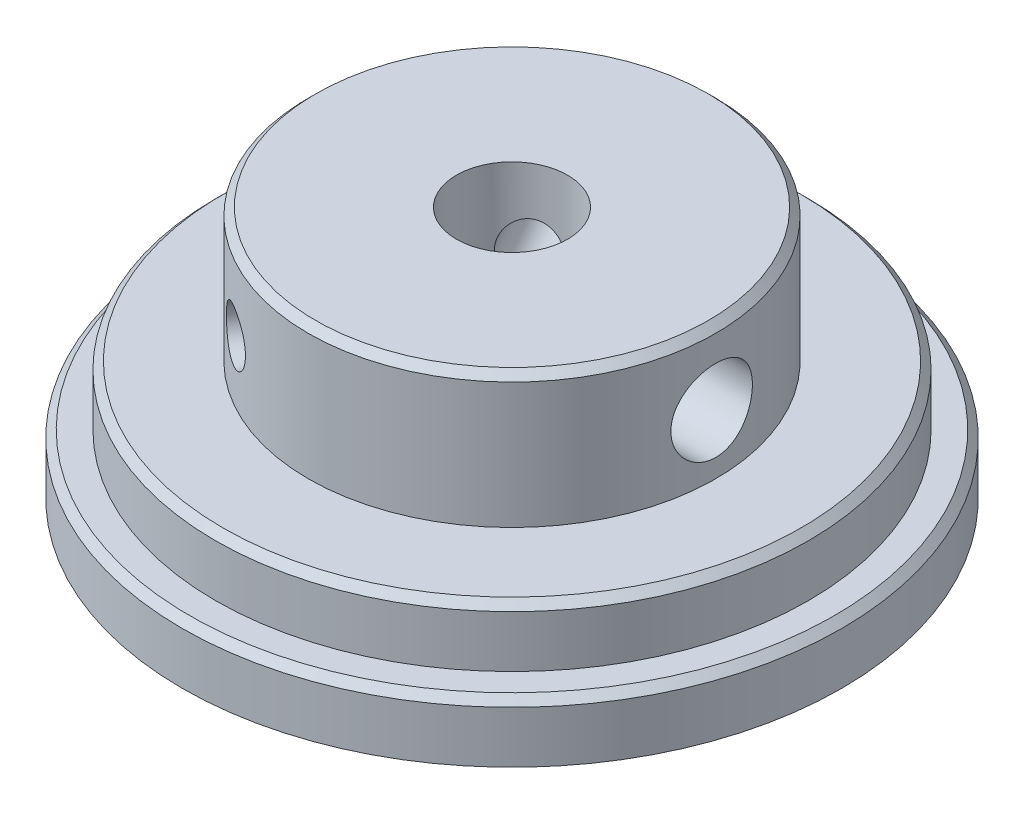
SolidWorks part; units mm, degrees
ref_plane "Piano frontale" through (0, 0, 0) normal (0, 0, 1) x (1, 0, 0)
ref_plane "Piano superiore" through (0, 0, 0) normal (0, 1, 0) x (1, 0, 0)
ref_plane "Piano destro" through (0, 0, 0) normal (1, 0, 0) x (0, 0, -1)
sketch "Schizzo2" plane through (0, 0, 0) normal (0, 0, 1) x (1, 0, 0)
  line L0 (0, 38.3941) -> (0, -24.0435) construction
  line L1 (7.5, 0) -> (44.5, 0)
  line L2 (44.5, 0) -> (44.5, 8)
  line L3 (44.5, 8) -> (40, 8)
  line L4 (40, 8) -> (40, 16)
  line L5 (40, 16) -> (27.5, 16)
  line L6 (27.5, 16) -> (27.5, 34)
  line L7 (27.5, 34) -> (7.5, 34)
  line L8 (7.5, 34) -> (7.5, 0)
  dimension "D1" = 55
  dimension "D2" = 16
  dimension "D3" = 34
  dimension "D4" = 80
  dimension "D5" = 8
  dimension "D6" = 89
  dimension "D7" = 15
revolve "Rivoluzione1" add sketch "Schizzo2" angle 360 about L0
ref_plane "Piano1" through (27.5, 0, 0) normal (1, 0, 0) x (0, 0, -1)
hole_wizard "Foro Ø11.0 (11)-1" positions "Schizzo3" profile "Schizzo4" hole size "Ø11.0" standard "ISO"
sketch "Schizzo3" plane through (27.5, 0, 0) normal (1, 0, 0) x (0, 0, -1)
  line L0 (0, 34) -> (0, 16) construction
  line L1 (27.5, 34) -> (-27.5, 34) construction
  line L2 (40, 16) -> (-40, 16) construction
  point P7 (0, 24)
  dimension "D1" = 10
sketch "Schizzo4" plane through (27.5, 24, 0) normal (0, 1, 0) x (0, 0, -1)
  line L0 (0, 0) -> (0, 20)
  line L1 (0, 20) -> (5.5, 20)
  line L2 (5.5, 20) -> (5.5, 0)
  line L5 (5.5, 0) -> (0, 0)
  line L11 (0, -6.35) -> (0, 107.95) construction
  dimension "Thru Hole Dia." = 11
  dimension "Thru Hole Depth" = 20
ref_plane "Piano2" through (-13.75, 0, 23.8157) normal (-0.5, 0, 0.866) x (0, 1, 0)
hole_wizard "Foro Ø7.0 (7)-1" positions "Schizzo5" profile "Schizzo6" hole size "Ø7.0" standard "ISO"
sketch "Schizzo5" plane through (-13.75, 0, 23.8157) normal (-0.5, 0, 0.866) x (0, 1, 0)
  line L0 (0, 0) -> (34, 0) construction
  line L1 (34, -27.5) -> (34, 27.5) construction
  point P8 (24, 0)
  dimension "D1" = 10
sketch "Schizzo6" plane through (-13.75, 24, 23.8157) normal (0, 1, 0) x (0.866, 0, 0.5)
  line L0 (0, 0) -> (0, 20)
  line L1 (0, 20) -> (3.5, 20)
  line L2 (3.5, 20) -> (3.5, 0)
  line L5 (3.5, 0) -> (0, 0)
  line L11 (0, -6.35) -> (0, 107.95) construction
  dimension "Thru Hole Dia." = 7
  dimension "Thru Hole Depth" = 20
mirror "Specchia1" about plane through (0, 0, 0) normal (0, 0, 1) of "Foro Ø7.0 (7)-1"
chamfer "Smusso1" distance 1 angle 45 3 edges at (0, 8, 44.5) (0, 16, 40) (0, 34, 27.5)
